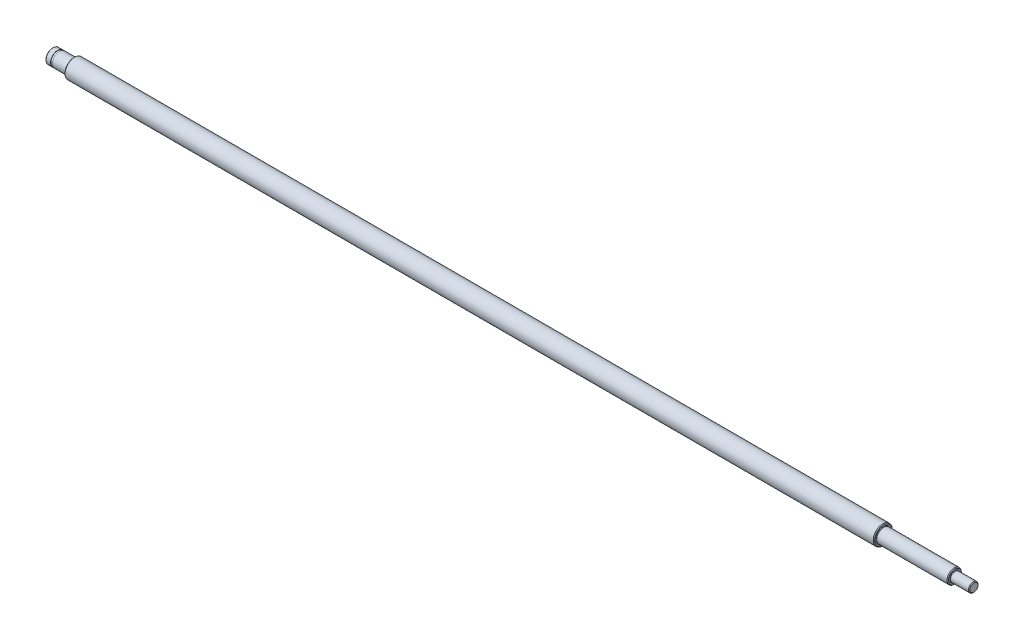
SolidWorks part; units mm, degrees
material "6061 合金"
ref_plane "前视基准面" through (0, 0, 0) normal (0, 0, 1) x (1, 0, 0)
ref_plane "上视基准面" through (0, 0, 0) normal (0, 1, 0) x (1, 0, 0)
ref_plane "右视基准面" through (0, 0, 0) normal (1, 0, 0) x (0, 0, -1)
other "Configuration Table"
ref_plane "基准面1" through (0, 0, 0) normal (0, 0, -1) x (-1, 0, 0)
sketch "草图1" plane through (0, 0, 0) normal (0, 0, -1) x (-1, 0, 0)
  line L0 (-387, 1.7) -> (-387, 0)
  line L1 (-387, 0) -> (0, 0)
  line L2 (0, 0) -> (0, 2.7)
  line L3 (0, 2.7) -> (-0.3, 3)
  line L4 (-0.3, 3) -> (-2.2, 3)
  line L5 (-2.2, 3) -> (-2.2, 2.85)
  line L6 (-2.2, 2.85) -> (-3, 2.85)
  line L7 (-3, 2.85) -> (-3, 3)
  line L8 (-3, 3) -> (-8.8, 3)
  line L9 (-9, 3.2) -> (-9, 3.7)
  line L10 (-9, 3.7) -> (-9.3, 4)
  line L11 (-9.3, 4) -> (-348.7, 4)
  line L12 (-348.7, 4) -> (-349, 3.7)
  line L13 (-349, 3.7) -> (-349, 3.2)
  line L14 (-349.2, 3) -> (-378.7, 3)
  line L15 (-378.7, 3) -> (-379, 2.7)
  line L16 (-379, 2.7) -> (-379, 2.2)
  line L17 (-379.2, 2) -> (-386.7, 2)
  line L18 (-386.7, 2) -> (-387, 1.7)
  line L19 (-387, 0) -> (0, 0) construction
  arc A0 (-8.8, 3) -> (-9, 3.2) centre (-8.8, 3.2) cw
  arc A1 (-349, 3.2) -> (-349.2, 3) centre (-349.2, 3.2) cw
  arc A2 (-379, 2.2) -> (-379.2, 2) centre (-379.2, 2.2) cw
  dimension "D1" = 5.8
  dimension "D2" = 1.9
  dimension "D3" = 0.8
  dimension "D4" = 2.7
  dimension "D5" = 0.3
  dimension "D6" = 0.5
  dimension "D7" = 29.5
  dimension "D8" = 339.4
revolve "旋转1" add sketch "草图1" angle 360 about L19
